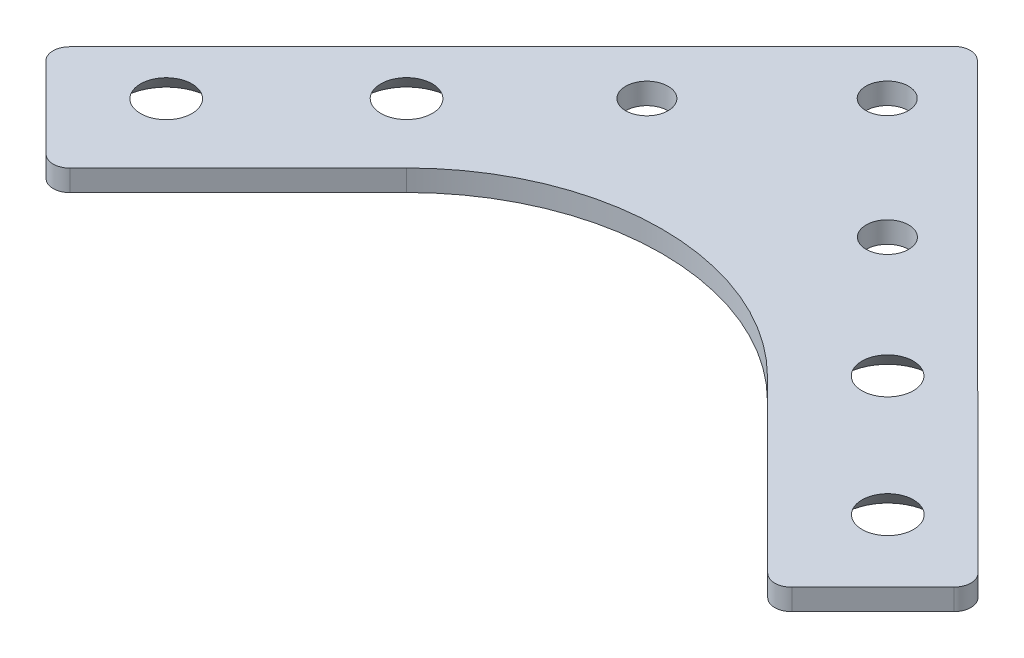
SolidWorks part; units mm, degrees
material "6061 Alloy"
ref_plane "Front Plane" through (0, 0, 0) normal (0, 0, 1) x (1, 0, 0)
ref_plane "Top Plane" through (0, 0, 0) normal (0, 1, 0) x (1, 0, 0)
ref_plane "Right Plane" through (0, 0, 0) normal (1, 0, 0) x (0, 0, -1)
sketch "Outline" plane through (0, 43.8334, 0) normal (0, -1, 0) x (1, 0, 0)
  line L0 (175.1714, -660.3981) -> (172.9281, -658.1513)
  line L1 (175.1714, -660.3981) -> (-309.3782, -175.0804) construction
  line L2 (172.9281, -658.1513) -> (175.175, -655.908)
  line L3 (176.9724, -654.1133) -> (243.4309, -587.7601)
  line L7 (227.7279, -572.0322) -> (202.162, -597.5577)
  line L8 (193.1461, -642.4518) -> (-291.4035, -157.1341) construction
  line L9 (148.2804, -597.515) -> (123.1556, -572.3504)
  line L12 (107.4278, -588.0534) -> (173.3803, -654.1105)
  line L16 (107.4306, -584.4613) -> (119.5635, -572.3475)
  line L18 (243.4337, -584.168) -> (231.32, -572.035)
  arc A0 (202.162, -597.5577) -> (148.2804, -597.515) centre (175.2425, -570.5956) cw
  arc A3 (176.9724, -654.1133) -> (173.3803, -654.1105) centre (175.1778, -652.3159) cw
  arc A4 (107.4306, -584.4613) -> (107.4278, -588.0534) centre (109.2252, -586.2587) ccw
  arc A5 (119.5635, -572.3475) -> (123.1556, -572.3504) centre (121.3582, -574.145) cw
  arc A6 (231.32, -572.035) -> (227.7279, -572.0322) centre (229.5225, -573.8296) ccw
  arc A7 (243.4337, -584.168) -> (243.4309, -587.7601) centre (241.6363, -585.9626) cw
  point P7 (0, 0)
  point P8 (0, 0)
  point P21 (175.1999, -624.4771)
  dimension "D1" = 38.1
  dimension "D2" = 2.54
  dimension "D3" = 2.54
  dimension "D4" = 2.54
  dimension "D5" = 2.54
  dimension "D6" = 2.54
extrude "Boss-Extrude1" add sketch "Outline" along normal blind 3.175 contours L3 A7 L18 A6 L7 A0 L9 A5 L16 A4 L12 A3
sketch "Hole Locations" plane through (0, 40.6584, 0) normal (0, -1, 0) x (1, 0, 0)
  line L0 (175.1856, -642.4376) -> (157.2394, -624.4629)
  line L1 (157.2394, -624.4629) -> (139.2931, -606.4881)
  line L2 (139.2931, -606.4881) -> (121.3468, -588.5134)
  line L5 (193.1604, -624.4913) -> (211.1351, -606.545)
  line L6 (211.1351, -606.545) -> (229.1098, -588.5987)
hole_wizard "1/4 (0.25) Diameter Hole1" positions "Sketch6" profile "Sketch7" hole size "1/4" standard "ANSI Inch" end condition through all
sketch "Sketch6" plane through (0, 40.6584, 0) normal (0, -1, 0) x (-1, 0, 0)
  point P0 (-175.1856, 642.4376)
  point P3 (-193.1604, 624.4913)
  point P6 (-157.2394, 624.4629)
sketch "Sketch7" plane through (175.1856, 40.6584, -642.4376) normal (1, 0, 0) x (0, 0, -1)
  line L0 (0, 0) -> (0, 3.175)
  line L1 (0, 3.175) -> (3.175, 3.175)
  line L2 (3.175, 3.175) -> (3.175, 0)
  line L5 (3.175, 0) -> (0, 0)
  line L11 (0, -6.35) -> (0, 107.95) construction
  dimension "Thru Hole Dia." = 6.35
  dimension "Thru Hole Depth" = 3.175
hole_wizard "1/4 (0.25) Diameter Hole3" positions "Sketch10" profile "Sketch11" hole size "1/4" standard "ANSI Inch" end condition through all
sketch "Sketch10" plane through (0, 40.6584, 0) normal (0, -1, 0) x (-1, 0, 0)
  point P0 (-139.2931, 606.4881)
  point P3 (-121.3468, 588.5134)
  point P6 (-211.1351, 606.545)
  point P9 (-229.1098, 588.5987)
sketch "Sketch11" plane through (139.2931, 40.6584, -606.4881) normal (1, 0, 0) x (0, 0, -1)
  line L0 (0, 0) -> (0, 3.175)
  line L1 (0, 3.175) -> (3.175, 3.175)
  line L2 (3.175, 3.175) -> (3.175, 3.9446)
  line L3 (3.175, 3.9446) -> (6.604, 0)
  line L5 (6.604, 0) -> (0, 0)
  line L6 (-3.175, 3.9446) -> (-6.604, 0) construction
  line L11 (0, -6.35) -> (0, 107.95) construction
  dimension "Thru Hole Dia." = 6.35
  dimension "Thru Hole Depth" = 3.175
  dimension "Near C'Sink Dia." = 13.208
  dimension "Near C'Sink Angle" = 82
